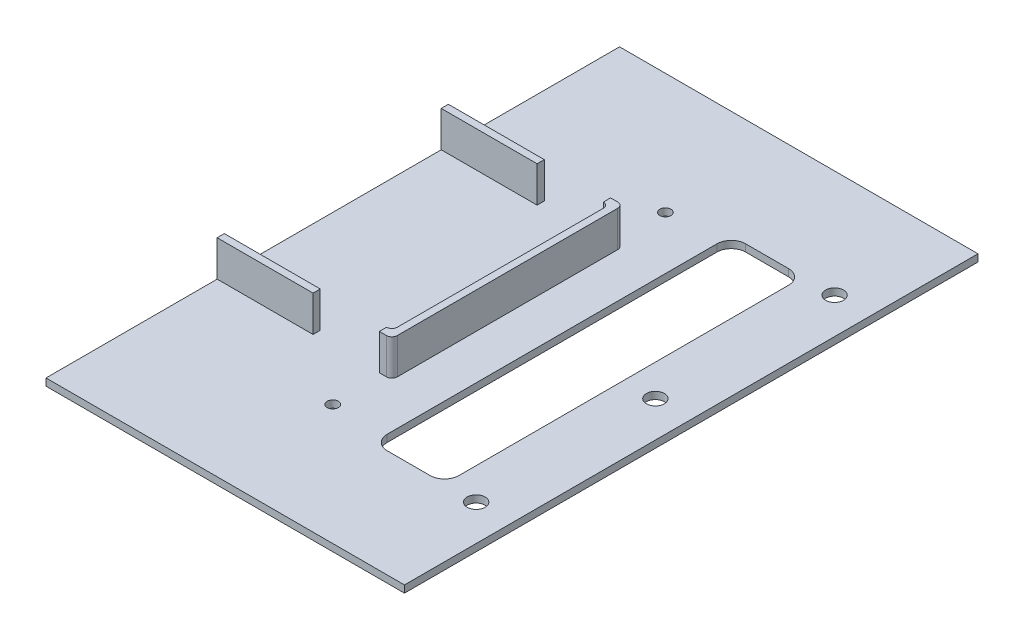
SolidWorks part; units mm, degrees
ref_plane "前视基准面" through (0, 0, 0) normal (0, 0, 1) x (1, 0, 0)
ref_plane "上视基准面" through (0, 0, 0) normal (0, 1, 0) x (1, 0, 0)
ref_plane "右视基准面" through (0, 0, 0) normal (1, 0, 0) x (0, 0, -1)
other "Configuration Table"
sketch "草图1" plane through (0, 0, 0) normal (0, 1, 0) x (1, 0, 0)
  line L0 (0, 120) -> (0, -49880) construction
  line L1 (-100, -120) -> (100, -120)
  line L2 (-100, -120) -> (-100, 120)
  line L3 (-100, 120) -> (100, 120)
  line L4 (100, -120) -> (100, 120)
  line L5 (-100, -120) -> (100, 120) construction
  line L6 (-100, 120) -> (100, -120) construction
  line L7 (-100, 120) -> (-70, 120)
  line L8 (-100, 120) -> (-100, 80)
  line L9 (-100, 80) -> (-70, 80)
  line L10 (-70, 120) -> (-70, 80)
  line L11 (-65, 0) -> (49935, 0) construction
  line L12 (-70, 120) -> (-70, 113)
  line L13 (-70, 113) -> (-70, 87)
  line L14 (-70, 87) -> (-70, 80)
  line L15 (-70, 113) -> (-40, 113)
  line L16 (-40, 113) -> (-40, 87)
  line L17 (-40, 87) -> (-70, 87)
  line L18 (-70, 113) -> (-70, 108)
  line L19 (-70, 87) -> (-70, 92)
  line L20 (-40, 87) -> (-48, 87)
  line L21 (-48, 87) -> (-48, 92)
  line L22 (-48, 92) -> (-40, 92)
  line L23 (-70, 92) -> (-62, 92)
  line L24 (-62, 92) -> (-62, 87)
  line L25 (-70, 100) -> (-40, 100) construction
  line L26 (0, 120) -> (0, 0)
  line L27 (0, 0) -> (-100, 0)
  line L28 (-70, 80) -> (0, 80)
  line L29 (100, 80) -> (70, 80)
  line L30 (70, 120) -> (70, 80)
  line L31 (100, -80) -> (70, -80)
  line L32 (70, -120) -> (70, -80)
  line L33 (-70, -120) -> (-70, -80)
  line L34 (-100, -80) -> (-70, -80)
  line L35 (0, 120) -> (0, 100)
  line L36 (0, 100) -> (-25, 100)
  line L37 (-25, 100) -> (-25, 115)
  line L38 (-25, 100) -> (-25, 85)
  line L39 (-25, 85) -> (-5, 85)
  line L40 (-25, 115) -> (-5, 115)
  line L41 (-5, 115) -> (-5, 85)
  line L42 (5, 115) -> (5, 85)
  line L43 (25, 100) -> (25, 85)
  line L44 (25, 85) -> (5, 85)
  line L45 (25, 115) -> (5, 115)
  line L46 (25, 100) -> (25, 115)
  line L47 (25, -85) -> (5, -85)
  line L48 (25, -100) -> (25, -85)
  line L49 (25, -100) -> (25, -115)
  line L50 (25, -115) -> (5, -115)
  line L51 (5, -115) -> (5, -85)
  line L52 (-25, -100) -> (-25, -115)
  line L53 (-25, -100) -> (-25, -85)
  line L54 (-25, -85) -> (-5, -85)
  line L55 (-5, -115) -> (-5, -85)
  line L56 (-25, -115) -> (-5, -115)
  line L57 (-100, 0) -> (-90, 0)
  line L58 (0, 120) -> (0, 100)
  line L59 (0, 120) -> (0, 110)
  line L60 (-70, 80) -> (70, 80)
  line L61 (-70, -80) -> (70, -80)
  line L62 (0, 0) -> (0, -120)
  circle A0 centre (-62, 92) radius 1.7
  circle A1 centre (-48, 92) radius 1.7
  circle A2 centre (-48, 108) radius 1.7
  circle A3 centre (-62, 108) radius 1.7
  circle A4 centre (48, 108) radius 1.7
  circle A5 centre (48, 92) radius 1.7
  circle A6 centre (62, 92) radius 1.7
  circle A7 centre (62, 108) radius 1.7
  circle A8 centre (62, -108) radius 1.7
  circle A9 centre (62, -92) radius 1.7
  circle A10 centre (48, -92) radius 1.7
  circle A11 centre (48, -108) radius 1.7
  circle A12 centre (-48, -92) radius 1.7
  circle A13 centre (-62, -92) radius 1.7
  circle A14 centre (-48, -108) radius 1.7
  circle A15 centre (-62, -108) radius 1.7
  circle A16 centre (-90, 0) radius 2.5
  circle A17 centre (-90, 50) radius 2.5
  circle A18 centre (-90, -50) radius 2.5
  circle A19 centre (90, -50) radius 2.5
  circle A20 centre (90, 0) radius 2.5
  circle A21 centre (90, 50) radius 2.5
  circle A22 centre (0, 110) radius 2.5
  circle A23 centre (35, 110) radius 2.5
  point P0 (0, 0)
  point P11 (0, 120)
  point P14 (-100, 0)
  point P15 (100, 0)
  dimension "D12" = 3.4
  dimension "D13" = 3.4
  dimension "D19" = 5
  dimension "D23" = 5
  dimension "D1" = 200
  dimension "D2" = 240
  dimension "D3" = 30
  dimension "D4" = 40
  dimension "D5" = 7
  dimension "D6" = 7
  dimension "D7" = 30
  dimension "D8" = 5
  dimension "D9" = 5
  dimension "D10" = 8
  dimension "D11" = 8
  dimension "D14" = 25
  dimension "D15" = 15
  dimension "D16" = 15
  dimension "D17" = 20
  dimension "D18" = 10
  dimension "D21" = 20
  dimension "D22" = 10
  dimension "D20" = 2
  dimension "D24" = 2
extrude "凸台-拉伸4" add sketch "草图1" along normal blind 2 contours L26 L62 L61 L31 L4 L29 L60 A20 A19 A21
sketch "草图4" plane through (0, 2, 0) normal (0, 1, 0) x (1, 0, 0)
  line L0 (-1000, 0) -> (49000, 0) construction
  line L1 (-50, -50) -> (50, -50)
  line L2 (-50, -50) -> (-50, 50)
  line L3 (-50, 50) -> (50, 50)
  line L4 (50, -50) -> (50, 50)
  line L5 (-50, -50) -> (50, 50) construction
  line L6 (-50, 50) -> (50, -50) construction
  line L7 (50, 50) -> (47.4, 50)
  line L8 (50, 50) -> (50, 47.4)
  line L9 (50, 47.4) -> (47.4, 47.4)
  line L10 (47.4, 50) -> (47.4, 47.4)
  line L12 (65.178, 50) -> (77.178, 50)
  line L13 (50, 50) -> (50, -50)
  line L14 (65.178, -50) -> (77.178, -50)
  line L15 (81.178, 46) -> (81.178, -46)
  line L16 (81.178, 50) -> (61.178, 50)
  line L17 (81.178, 50) -> (81.178, -50)
  line L18 (81.178, -50) -> (61.178, -50)
  line L19 (61.178, 46) -> (61.178, -46)
  circle A0 centre (47.4, 47.4) radius 1.5
  circle A1 centre (47.4, -47.4) radius 1.5
  arc A2 (77.178, -50) -> (81.178, -46) centre (77.178, -46) ccw
  arc A3 (65.178, -50) -> (61.178, -46) centre (65.178, -46) cw
  arc A4 (81.178, 46) -> (77.178, 50) centre (77.178, 46) ccw
  arc A5 (65.178, 50) -> (61.178, 46) centre (65.178, 46) ccw
  point P0 (0, 0)
  dimension "D4" = 3
  dimension "D6" = 4
  dimension "D3" = 2.6
extrude "切除-拉伸2" cut sketch "草图4" against normal blind 2 contours L12 A5 L19 A3 L14 A2 L15 A4 | A1 | A0
sketch "草图6" plane through (0, 2, 0) normal (0, 1, 0) x (1, 0, 0)
  line L0 (-47.25, 32.25) -> (47.25, 32.25)
  line L1 (-45.25, -30.25) -> (45.25, -30.25)
  line L2 (-46.75, -28.75) -> (-46.75, 28.75)
  line L3 (-45.25, 30.25) -> (45.25, 30.25)
  line L4 (46.75, -28.75) -> (46.75, 28.75)
  line L5 (-46.75, -30.25) -> (46.75, 30.25) construction
  line L6 (-46.75, 30.25) -> (46.75, -30.25) construction
  line L7 (48.75, -30.75) -> (48.75, 30.75)
  line L8 (-47.25, -32.25) -> (47.25, -32.25)
  line L9 (-48.75, -30.75) -> (-48.75, 30.75)
  line L10 (0, -1000) -> (0, 49000) construction
  line L11 (48.75, -32.25) -> (48.75, 32.25) construction
  line L12 (-48.75, 32.25) -> (48.75, 32.25) construction
  line L13 (-48.75, -32.25) -> (48.75, -32.25) construction
  line L14 (-48.75, -32.25) -> (-48.75, 32.25) construction
  line L15 (-46.75, -30.25) -> (-46.75, 30.25) construction
  line L16 (-46.75, 30.25) -> (46.75, 30.25) construction
  line L17 (-46.75, -30.25) -> (46.75, -30.25) construction
  line L18 (46.75, -30.25) -> (46.75, 30.25) construction
  line L19 (46.75, -28.75) -> (46.75, -32.25)
  line L20 (46.75, -32.25) -> (26.75, -32.25)
  line L21 (26.75, -32.25) -> (26.75, -30.25)
  line L22 (-1000, 0) -> (49000, 0) construction
  line L23 (46.75, 28.75) -> (46.75, 32.25)
  line L24 (26.75, 32.25) -> (26.75, 30.25)
  line L25 (45.25, -30.25) -> (45.25, -32.25)
  line L26 (45.25, 30.25) -> (45.25, 32.25)
  arc A0 (48.75, 30.75) -> (47.25, 32.25) centre (47.25, 30.75) ccw
  arc A1 (47.25, -32.25) -> (48.75, -30.75) centre (47.25, -30.75) ccw
  arc A2 (-48.75, -30.75) -> (-47.25, -32.25) centre (-47.25, -30.75) ccw
  arc A3 (-47.25, 32.25) -> (-48.75, 30.75) centre (-47.25, 30.75) ccw
  arc A4 (-46.75, 28.75) -> (-45.25, 30.25) centre (-45.25, 28.75) cw
  arc A5 (-46.75, -28.75) -> (-45.25, -30.25) centre (-45.25, -28.75) ccw
  arc A6 (46.75, -28.75) -> (45.25, -30.25) centre (45.25, -28.75) cw
  arc A7 (45.25, 30.25) -> (46.75, 28.75) centre (45.25, 28.75) cw
  point P0 (0, 0)
  line M7 (0, 80) -> (0, -80)
  dimension "D4" = 1.5
  dimension "D1" = 20
  dimension "D3" = 2
extrude "凸台-拉伸5" add sketch "草图6" along normal blind 10 contours L8 L21 L1 M7 | L8 A1 L7 A0 L0 L23 L4 L19 | L19 A6 L25 L20 | L26 A7 L23 L0 | L24 L0 L3 M7
sketch "草图7" plane through (0, 2, 0) normal (0, 1, 0) x (1, 0, 0)
  circle A0 centre (47.4, 47.4) radius 1.5
  circle A1 centre (47.4, -47.4) radius 1.6632
extrude "凸台-拉伸6" add sketch "草图7" against normal blind 2
sketch "草图8" plane through (0, 2, 0) normal (0, 1, 0) x (1, 0, 0)
  line L0 (-998.0276, 0) -> (49001.9724, 0) construction
  line L1 (50, 50) -> (46.4, 50)
  line L2 (50, 50) -> (50, 46.4)
  line L3 (50, 46.4) -> (46.4, 46.4)
  line L4 (46.4, 50) -> (46.4, 46.4)
  circle A0 centre (46.4, 46.4) radius 1.55
  circle A1 centre (46.4, -46.4) radius 1.55
  dimension "D3" = 3.1
  dimension "D1" = 3.6
  dimension "D2" = 3.6
extrude "切除-拉伸3" cut sketch "草图8" against normal blind 2 contours L4 A0 L3 | L3 A0 L4 | A1
